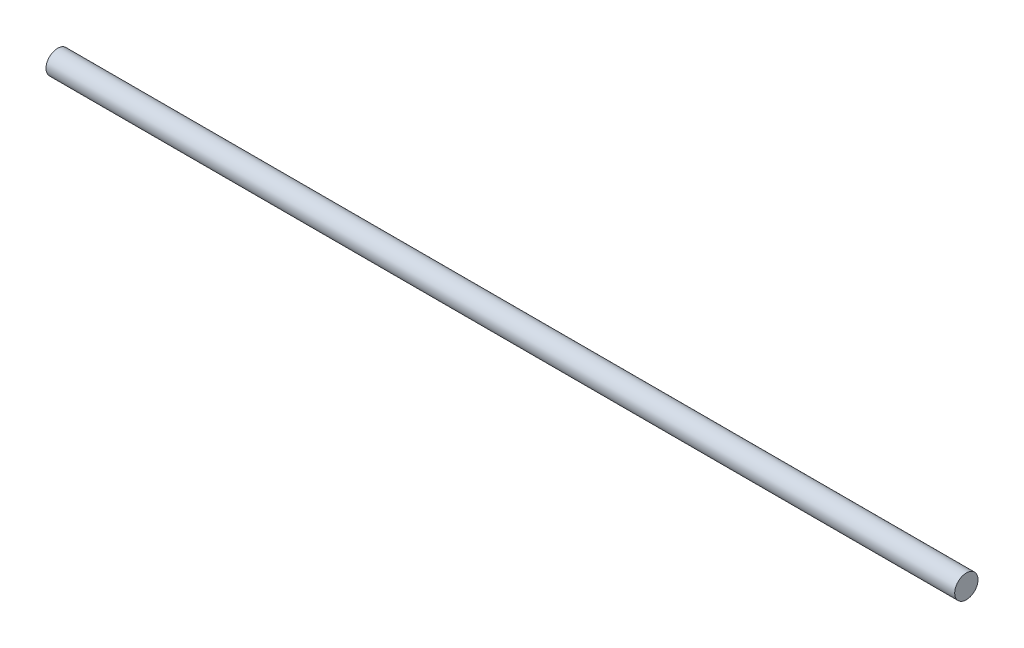
SolidWorks part; units mm, degrees
ref_plane "Front Plane" through (0, 0, 0) normal (0, 0, 1) x (1, 0, 0)
ref_plane "Top Plane" through (0, 0, 0) normal (0, 1, 0) x (1, 0, 0)
ref_plane "Right Plane" through (0, 0, 0) normal (1, 0, 0) x (0, 0, -1)
sketch "Sketch1" plane through (0, 0, 0) normal (1, 0, 0) x (0, 0, -1)
  circle A0 centre (0, 0) radius 5
  dimension "D1" = 10
extrude "Boss-Extrude1" add sketch "Sketch1" along normal blind 390
